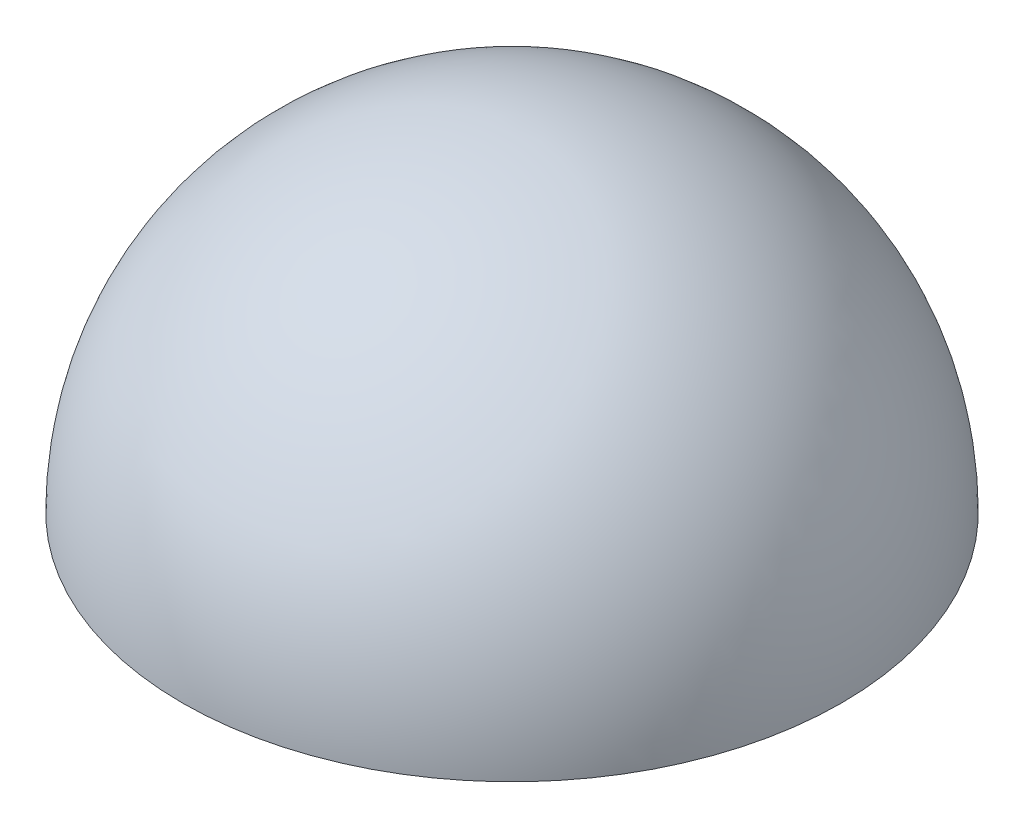
SolidWorks part; units mm, degrees
ref_plane "Alzado" through (0, 0, 0) normal (0, 0, 1) x (1, 0, 0)
ref_plane "Planta" through (0, 0, 0) normal (0, 1, 0) x (1, 0, 0)
ref_plane "Vista lateral" through (0, 0, 0) normal (1, 0, 0) x (0, 0, -1)
sketch "Croquis_perfil" plane through (0, 0, 0) normal (0, 0, 1) x (1, 0, 0)
  line L0 (0, 0) -> (0, 60) construction
  line L1 (0, 0) -> (60, 0)
  line L2 (0, 60) -> (0, 0)
  arc A0 (60, 0) -> (0, 60) centre (0, 0) ccw
  dimension "D1" = 60
revolve "Domo_D120" add sketch "Croquis_perfil" angle 360 about L0
sketch "Croquis_agujeros_montaje" plane through (0, 0, 0) normal (0, 1, 0) x (1, 0, 0)
  circle A0 centre (0, 0) radius 4
  dimension "D1" = 8
extrude "Agujero_inserto_M6" cut sketch "Croquis_agujeros_montaje" along normal blind 14
